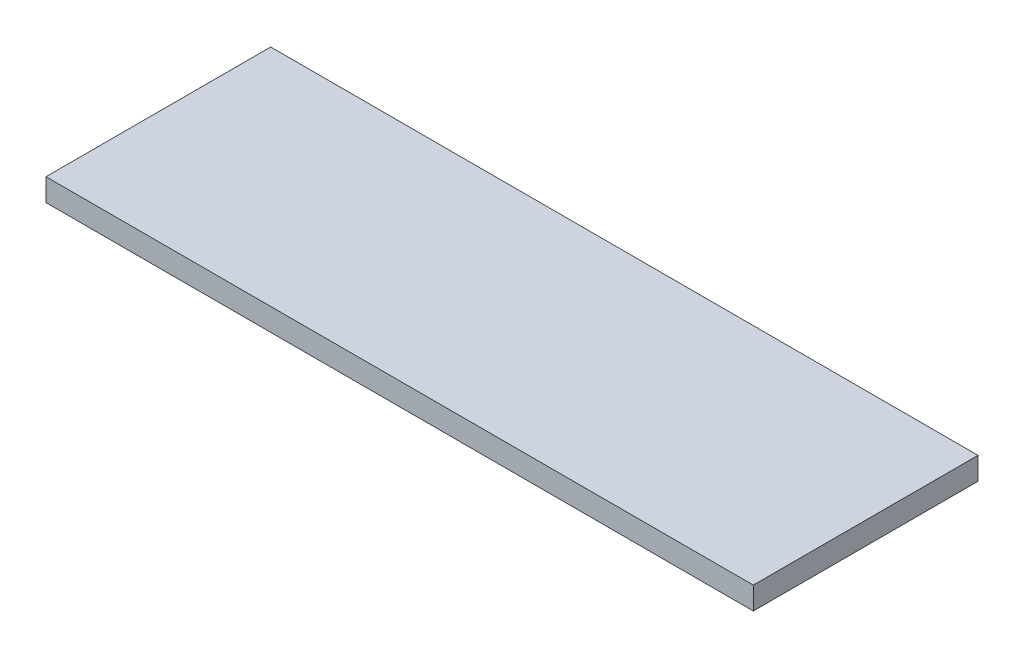
SolidWorks part; units mm, degrees
ref_plane "Front Plane" through (0, 0, 0) normal (0, 0, 1) x (1, 0, 0)
ref_plane "Top Plane" through (0, 0, 0) normal (0, 1, 0) x (1, 0, 0)
ref_plane "Right Plane" through (0, 0, 0) normal (1, 0, 0) x (0, 0, -1)
sketch "Sketch1" plane through (0, 0, 0) normal (0, 1, 0) x (1, 0, 0)
  line L1 (-236.1, -75) -> (236.1, -75)
  line L2 (-236.1, -75) -> (-236.1, 75)
  line L3 (-236.1, 75) -> (236.1, 75)
  line L4 (236.1, -75) -> (236.1, 75)
  line L5 (-236.1, -75) -> (236.1, 75) construction
  line L6 (-236.1, 75) -> (236.1, -75) construction
  point P0 (0, 0)
  dimension "D1" = 472.2
  dimension "D2" = 150
extrude "Boss-Extrude1" add sketch "Sketch1" along normal blind 15
